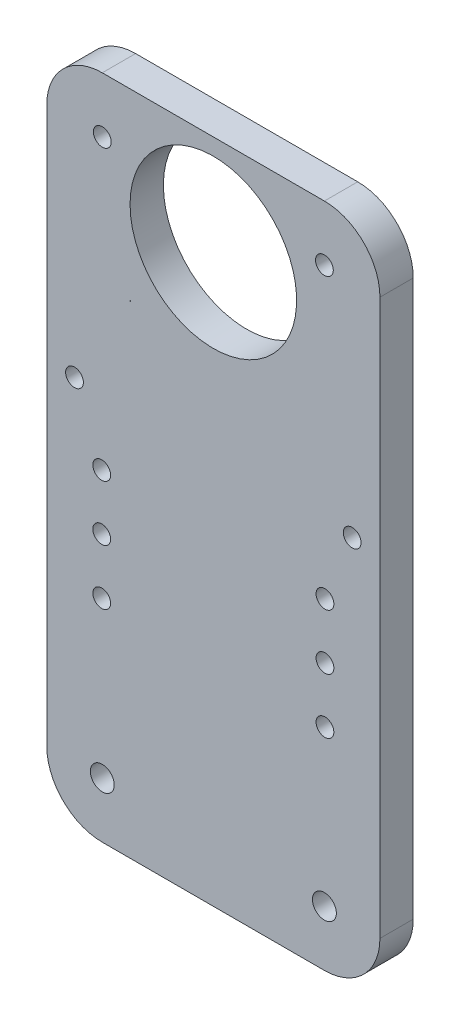
SolidWorks part; units mm, degrees
ref_plane "前视基准面" through (0, 0, 0) normal (0, 0, 1) x (1, 0, 0)
ref_plane "上视基准面" through (0, 0, 0) normal (0, 1, 0) x (1, 0, 0)
ref_plane "右视基准面" through (0, 0, 0) normal (1, 0, 0) x (0, 0, -1)
other "Configuration Table"
sketch "草图1" plane through (0, 0, 0) normal (0, 0, 1) x (1, 0, 0)
  line L0 (0, -60) -> (0, -50)
  line L5 (-30, -60) -> (30, -60)
  line L6 (-30, -60) -> (-30, 60)
  line L7 (0, -50) -> (20, -50)
  line L8 (-30, 60) -> (30, 60)
  line L9 (30, -60) -> (30, 60)
  line L10 (-30, -60) -> (30, 60) construction
  line L11 (-30, 60) -> (30, -60) construction
  line L12 (0, 60) -> (0, 10)
  line L13 (0, 35) -> (0, 42)
  line L14 (0, 42) -> (0, 28) construction
  line L15 (6, 42) -> (6, 28)
  line L16 (-6, 42) -> (-6, 28)
  circle A33 centre (0, 50.5) radius 1.6
  circle A34 centre (20, -50) radius 2.15
  circle A35 centre (-20, -50) radius 2.15
  circle A36 centre (0, 35) radius 19
  circle A37 centre (0, 35) radius 15.5
  circle A38 centre (13.4234, 42.75) radius 1.6
  circle A39 centre (13.4234, 27.25) radius 1.6
  circle A40 centre (0, 19.5) radius 1.6
  circle A41 centre (-13.4234, 27.25) radius 1.6
  circle A42 centre (-13.4234, 42.75) radius 1.6
  arc A43 (6, 42) -> (-6, 42) centre (0, 42) ccw
  arc A44 (-6, 28) -> (6, 28) centre (0, 28) ccw
  point P0 (0, 0)
  point P20 (0, 35)
  dimension "D5" = 4.3
  dimension "D8" = 31
  dimension "D9" = 3.2
  dimension "D10" = 6
  dimension "D13" = 6
  dimension "D7" = 38
  dimension "D1" = 60
  dimension "D2" = 120
  dimension "D3" = 10
  dimension "D4" = 20
  dimension "D6" = 50
  dimension "D11" = 7
  dimension "D12" = 14
extrude "凸台-拉伸3" add sketch "草图1" along normal blind 6
sketch "草图9" plane through (0, 0, 6) normal (0, 0, 1) x (1, 0, 0)
  line L0 (0, -972) -> (0, 49028) construction
  line L1 (-15, 28) -> (-15, -12)
  line L2 (-15, -12) -> (-20.1, -12)
  line L3 (-20, 28) -> (-20.1, -22)
  line L4 (-20.1, -22) -> (-25.1, -22)
  circle A0 centre (0, 28) radius 15
  circle A2 centre (-20.1, -12) radius 1.6
  circle A3 centre (20.1, -12) radius 1.6
  circle A4 centre (0, 28) radius 20
  circle A7 centre (-20.1, -2) radius 1.6
  circle A8 centre (20.1, -2) radius 1.6
  circle A13 centre (-20.1, -22) radius 1.6
  circle A14 centre (20.1, -22) radius 1.6
  dimension "D1" = 30
  dimension "D3" = 5.1
  dimension "D4" = 3.2
  dimension "D5" = 40
  dimension "D8" = 2
  dimension "D2" = 40
  dimension "D6" = 50
  dimension "D7" = 5
  dimension "D9" = 2
extrude "切除-拉伸1" cut sketch "草图9" against normal blind 6 contours A14 | A8 | A3 | A7 | A2 | A13
fillet "圆角1" radius 10 4 edges at (30, -60, 3) (-30, -60, 3) (30, 60, 3) (-30, 60, 3)
sketch "草图10" plane through (0, 0, 0) normal (0, 0, -1) x (-1, 0, 0)
  circle A0 centre (-20, 50) radius 1.6
  circle A1 centre (-25, 10) radius 1.6
  circle A2 centre (25, 10) radius 1.6
  circle A3 centre (20, 50) radius 1.6
extrude "切除-拉伸2" cut sketch "草图10" against normal blind 10
sketch "草图11" plane through (0, 0, 6) normal (0, 0, 1) x (1, 0, 0)
  circle A0 centre (0, 28) radius 15
  dimension "D1" = 30
extrude "切除-拉伸3" cut sketch "草图11" against normal blind 10
sketch "草图12" plane through (0, 0, 6) normal (0, 0, 1) x (1, 0, 0)
  circle A0 centre (0, 42) radius 6
  circle A1 centre (-13.4234, 42.75) radius 1.6
  circle A2 centre (0, 50.5) radius 1.6
  circle A3 centre (13.4234, 42.75) radius 1.6
  circle A4 centre (0, 28) radius 15
  arc M3 (-6, 42) -> (6, 42) centre (0, 42) cw
  circle M16 centre (-13.4234, 42.75) radius 1.6
  circle M17 centre (0, 50.5) radius 1.6
  circle M18 centre (13.4234, 42.75) radius 1.6
extrude "凸台-拉伸4" add sketch "草图12" against normal blind 6 contours A4 A0 M3 | M16 | M17 | M18
sketch "草图13" plane through (0, 0, 0) normal (0, 0, -1) x (-1, 0, 0)
  line L0 (0, 28) -> (0, 42)
  circle A0 centre (0, 42) radius 15
  circle A1 centre (0, 28) radius 15
  arc M18 (6, 41.7477) -> (14.9935, 27.5579) centre (0, 28) cw
  arc M20 (14.9494, 26.7691) -> (-14.9494, 26.7691) centre (0, 28) cw
  arc M22 (-14.9935, 27.5579) -> (-6, 41.7477) centre (0, 28) cw
  dimension "D2" = 30
  dimension "D1" = 14
extrude "凸台-拉伸5" add sketch "草图13" against normal blind 6 contours A1 A0 M22 M20 M18
sketch "草图14" plane through (0, 0, 0) normal (0, 0, -1) x (-1, 0, 0)
  circle A0 centre (0, 42) radius 15
extrude "切除-拉伸4" cut sketch "草图14" against normal through all
